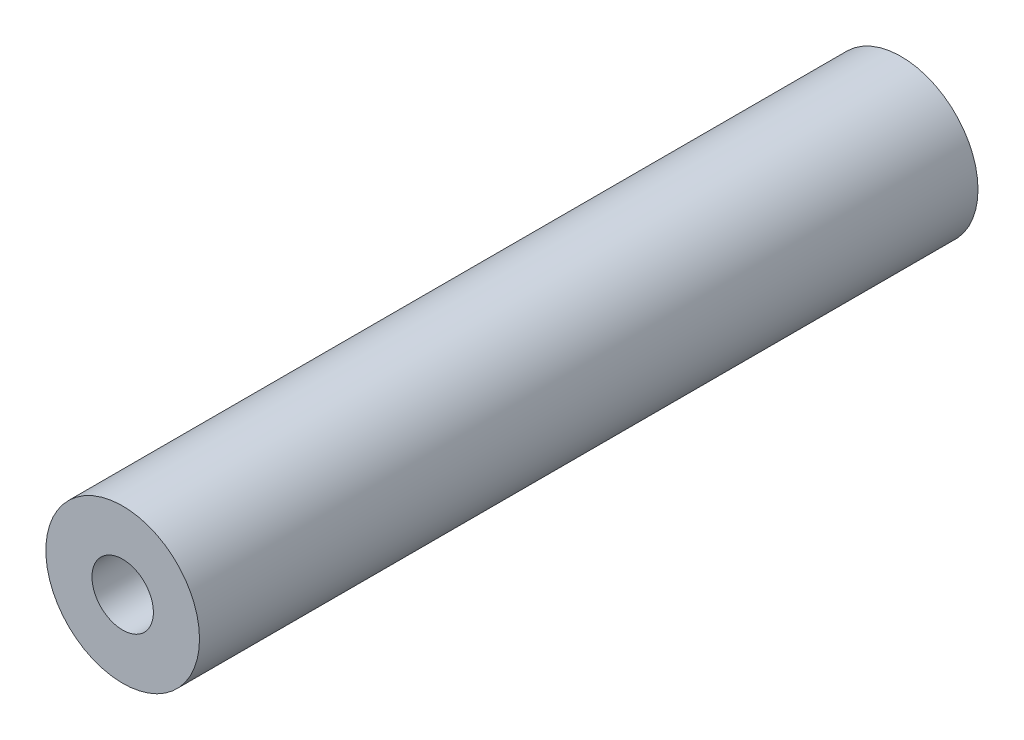
SolidWorks part; units mm, degrees
ref_plane "Płaszczyzna przednia" through (0, 0, 0) normal (0, 0, 1) x (1, 0, 0)
ref_plane "Płaszczyzna górna" through (0, 0, 0) normal (0, 1, 0) x (1, 0, 0)
ref_plane "Płaszczyzna prawa" through (0, 0, 0) normal (1, 0, 0) x (0, 0, -1)
sketch "Szkic1" plane through (0, 0, 0) normal (0, 0, 1) x (1, 0, 0)
  circle A0 centre (0, 0) radius 15
extrude "Dodanie-wyciągnięcie1" add sketch "Szkic1" along normal blind 152
sketch "Szkic2" plane through (0, 0, 0) normal (0, 0, -1) x (-1, 0, 0)
  circle A0 centre (0, 0) radius 6
extrude "Wytnij-wyciągnięcie1" cut sketch "Szkic2" against normal blind 55
sketch "Szkic3" plane through (0, 0, 152) normal (0, 0, 1) x (1, 0, 0)
  circle A0 centre (0, 0) radius 6
extrude "Wytnij-wyciągnięcie2" cut sketch "Szkic3" against normal blind 55
